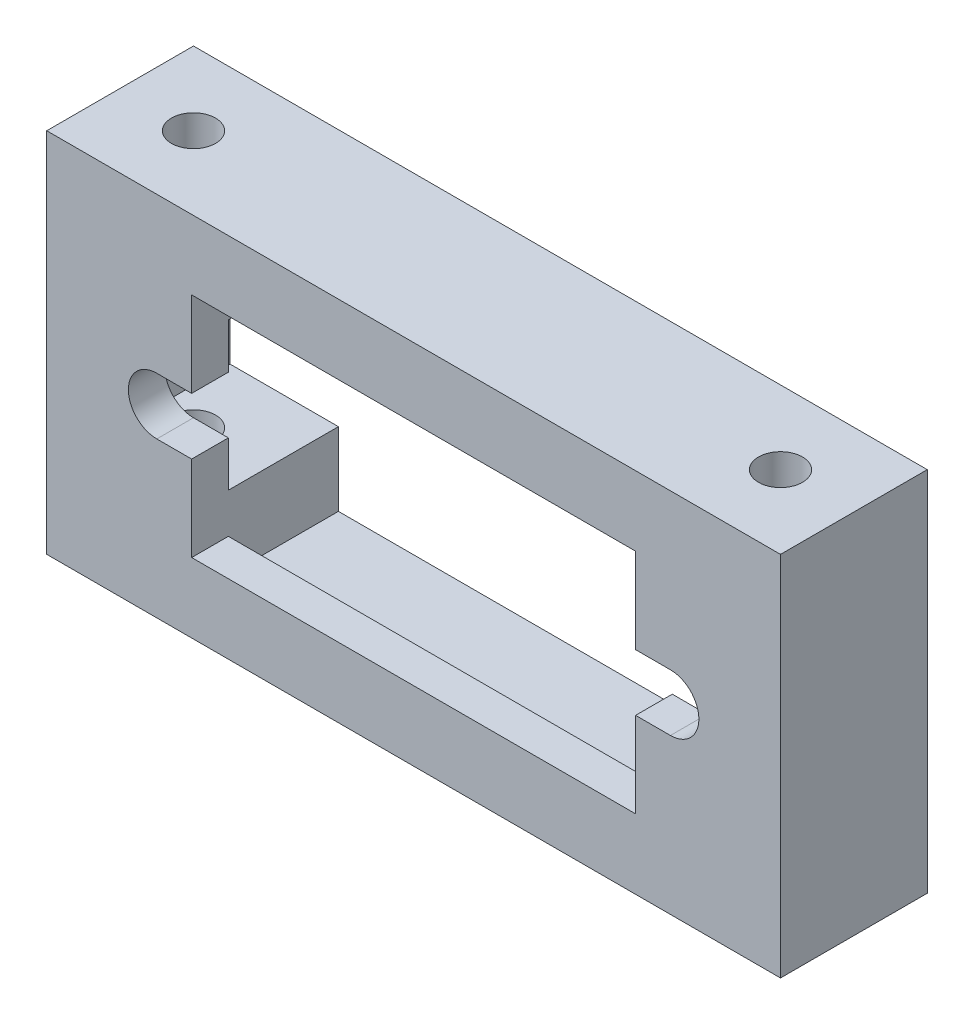
SolidWorks part; units mm, degrees
ref_plane "正面" through (0, 0, 0) normal (0, 0, 1) x (1, 0, 0)
ref_plane "平面" through (0, 0, 0) normal (0, 1, 0) x (1, 0, 0)
ref_plane "右側面" through (0, 0, 0) normal (1, 0, 0) x (0, 0, -1)
sketch "ｽｹｯﾁ1" plane through (0, 0, 0) normal (0, 0, 1) x (1, 0, 0)
  line L1 (-20, 10) -> (20, 10)
  line L2 (-20, 10) -> (-20, -10)
  line L3 (-20, -10) -> (20, -10)
  line L4 (20, 10) -> (20, -10)
  line L5 (-20, 10) -> (20, -10) construction
  line L6 (-20, -10) -> (20, 10) construction
  point P0 (0, 0)
  dimension "D1" = 20
  dimension "D2" = 40
extrude "ﾎﾞｽ - 押し出し1" add sketch "ｽｹｯﾁ1" along normal blind 2
sketch "ｽｹｯﾁ2" plane through (0, 0, 2) normal (0, 0, 1) x (1, 0, 0)
  line L5 (-12.1, 6.2) -> (12.1, 6.2)
  line L6 (-12.1, 6.2) -> (-12.1, -6.2)
  line L15 (-14, 1.55) -> (14, 1.55)
  line L16 (-14, 1.55) -> (-14, -1.55)
  line L17 (-14, -1.55) -> (14, -1.55)
  line L18 (14, 1.55) -> (14, -1.55)
  line L19 (-14, 1.55) -> (14, -1.55) construction
  line L20 (-14, -1.55) -> (14, 1.55) construction
  line L21 (-12.1, -6.2) -> (12.1, -6.2)
  line L22 (12.1, 6.2) -> (12.1, -6.2)
  line L23 (-12.1, 6.2) -> (12.1, -6.2) construction
  line L24 (-12.1, -6.2) -> (12.1, 6.2) construction
  arc A0 (14, 1.55) -> (14, -1.55) centre (14, 0) cw
  arc A1 (-14, 1.55) -> (-14, -1.55) centre (-14, 0) ccw
  point P0 (0, 0)
  point P1 (0, 0)
  dimension "D1" = 12.4
  dimension "D2" = 24.2
  dimension "D3" = 3.1
  dimension "D4" = 1.9
extrude "ｶｯﾄ - 押し出し1" cut sketch "ｽｹｯﾁ2" against normal blind 2 contours L15 L22 L17 L18 | L16 L17 L6 L15 | A0 L18 | L16 A1
sketch "ｽｹｯﾁ3" plane through (0, 0, 0) normal (0, 0, -1) x (-1, 0, 0)
  line L0 (20, 10) -> (20, -10) construction
  line L1 (20, 10) -> (18, 10)
  line L2 (20, 10) -> (20, -10)
  line L3 (20, -10) -> (18, -10)
  line L4 (18, 10) -> (18, -10)
  line L5 (20, -10) -> (-20, -10) construction
  line L7 (-20, 10) -> (-18, 10)
  line L8 (-20, 10) -> (-20, -10)
  line L9 (-20, -10) -> (-18, -10)
  line L10 (-18, 10) -> (-18, -10)
  dimension "D1" = 2
extrude "ﾎﾞｽ - 押し出し2" add sketch "ｽｹｯﾁ3" along normal blind 6
sketch "ｽｹｯﾁ5" plane through (0, 0, 0) normal (0, 0, -1) x (-1, 0, 0)
  line L0 (-18, -10) -> (-18, 10) construction
  line L1 (-18, 10) -> (18, 10)
  line L2 (-18, 10) -> (-18, 8.02)
  line L3 (-18, 8.02) -> (18, 8.02)
  line L4 (18, 10) -> (18, 8.02)
  line L5 (-18, 10) -> (18, 10) construction
  line L6 (18, 10) -> (18, -10) construction
  line L11 (-18, -10) -> (18, -10)
  line L12 (-18, -10) -> (-18, -8.02)
  line L13 (-18, -8.02) -> (18, -8.02)
  line L14 (18, -10) -> (18, -8.02)
  dimension "D2" = 1.98
extrude "ﾎﾞｽ - 押し出し3" add sketch "ｽｹｯﾁ5" along normal up to surface (6 mm away) up to face at (19, 0, -6)
sketch "ｽｹｯﾁ6" plane through (0, 0, 0) normal (0, 0, -1) x (-1, 0, 0)
  line L0 (-18, -8.02) -> (-18, 8.02) construction
  line L1 (-18, 8.02) -> (-12.1, 8.02)
  line L2 (-18, 8.02) -> (-18, 4.02)
  line L3 (-18, 4.02) -> (-12.1, 4.02)
  line L4 (-12.1, 8.02) -> (-12.1, 4.02)
  line L5 (-18, -8.02) -> (-18, 8.02) construction
  line L6 (-12.1, 6.2) -> (-12.1, 1.55) construction
  line L7 (18, 8.02) -> (18, -8.02) construction
  line L8 (18, 8.02) -> (12.1, 8.02)
  line L9 (18, 8.02) -> (18, 4.02)
  line L10 (18, 4.02) -> (12.1, 4.02)
  line L11 (12.1, 8.02) -> (12.1, 4.02)
  line L12 (18, 8.02) -> (18, -8.02) construction
  line L13 (12.1, 6.2) -> (12.1, 1.55) construction
  line L14 (12.1, -1.55) -> (12.1, -6.2) construction
  line L15 (18, -8.02) -> (12.1, -8.02)
  line L16 (18, -8.02) -> (18, -4.02)
  line L17 (18, -4.02) -> (12.1, -4.02)
  line L18 (12.1, -8.02) -> (12.1, -4.02)
  line L19 (-12.1, -1.55) -> (-12.1, -6.2) construction
  line L20 (-18, -8.02) -> (-12.1, -8.02)
  line L21 (-18, -8.02) -> (-18, -4.02)
  line L22 (-18, -4.02) -> (-12.1, -4.02)
  line L23 (-12.1, -8.02) -> (-12.1, -4.02)
  line L26 (-18, 8.02) -> (18, 8.02) construction
  line L27 (-18, 8.02) -> (18, 8.02) construction
  dimension "D1" = 4
extrude "ﾎﾞｽ - 押し出し4" add sketch "ｽｹｯﾁ6" along normal up to surface (6 mm away)
sketch "ｽｹｯﾁ7" plane through (0, 10, 0) normal (0, 1, 0) x (1, 0, 0)
  line L0 (-20, 2) -> (20, 2) construction
  line L1 (-20, -2) -> (-20, 6) construction
  line L2 (20, -2) -> (20, 6) construction
  circle A0 centre (-16, 2) radius 1.2
  circle A1 centre (16, 2) radius 1.2
  dimension "D1" = 2.4
  dimension "D2" = 4
  dimension "D3" = 4
extrude "ｶｯﾄ - 押し出し2" cut sketch "ｽｹｯﾁ7" against normal through all
